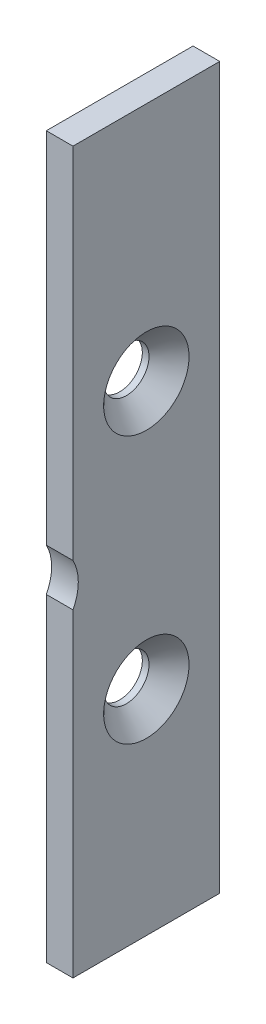
SolidWorks part; units mm, degrees
other "Preload Guide Rod End Stop"
ref_plane "Front Plane" through (0, 0, 0) normal (0, 0, 1) x (1, 0, 0)
ref_plane "Top Plane" through (0, 0, 0) normal (0, 1, 0) x (1, 0, 0)
ref_plane "Right Plane" through (0, 0, 0) normal (1, 0, 0) x (0, 0, -1)
sketch3d "End stop sheet sketch datum points"
  point P0 (58.2, -54.5, -33.5)
  point P1 (68.2, -54.5, -33.5)
  point P2 (58.2, -44.5, -33.5)
ref_plane "End stop sheet sketch plane" through (0, 0, -33.5) normal (0, 0, 1) x (1, 0, 0)
sketch "End stop sheet sketch" plane through (0, 0, -33.5) normal (0, 0, 1) x (1, 0, 0)
  line L0 (58.2, -54.5) -> (60.2, -54.5)
  line L1 (60.2, -54.5) -> (60.2, -0.5)
  line L2 (60.2, -0.5) -> (58.2, -0.5)
  line L3 (58.2, -0.5) -> (58.2, -54.5)
extrude "End stop sheet" add sketch "End stop sheet sketch" along normal blind 11 separate body
sketch3d "Screw end clearance sketch datum points"
  point P0 (58.1, -29, -19.5)
  point P1 (58.1, -19, -19.5)
  point P2 (58.1, -29, -9.5)
ref_plane "Screw end clearance sketch plane" through (58.1, 0, 0) normal (1, 0, 0) x (0, 0, -1)
sketch "Screw end clearance sketch" plane through (58.1, 0, 0) normal (1, 0, 0) x (0, 0, -1)
  circle A0 centre (19.5, -29) radius 3.4
extrude "Screw end clearance" cut sketch "Screw end clearance sketch" along normal blind 2.2
sketch3d "M3 countersunk clearance 1 bore profile datum points"
  point P0 (60.2, -18.5, -28)
  point P1 (60.2, -8.5, -28)
  point P2 (60.2, -18.5, -38)
ref_plane "M3 countersunk clearance 1 bore profile plane" through (60.2, 0, 0) normal (-1, 0, 0) x (0, 0, 1)
sketch "M3 countersunk clearance 1 bore profile" plane through (60.2, 0, 0) normal (-1, 0, 0) x (0, 0, 1)
  circle A0 centre (-28, -18.5) radius 1.7
extrude "M3 countersunk clearance 1 bore" cut sketch "M3 countersunk clearance 1 bore profile" along normal blind 2.2
sketch3d "M3 countersunk clearance 1 countersink axis line"
  line L0 (70.2, -18.5, -28) -> (50.2, -18.5, -28) construction
ref_axis "M3 countersunk clearance 1 countersink axis" through (70.2, -18.5, -28) along (-1, 0, 0)
sketch3d "M3 countersunk clearance 1 countersink profile datum points"
  point P0 (60.2, -18.5, -28)
  point P1 (60.2, -8.5, -28)
  point P2 (50.2, -18.5, -28)
ref_plane "M3 countersunk clearance 1 countersink profile plane" through (0, 0, -28) normal (0, 0, 1) x (1, 0, 0)
sketch "M3 countersunk clearance 1 countersink profile" plane through (0, 0, -28) normal (0, 0, 1) x (1, 0, 0)
  line L0 (60.2, -18.5) -> (60.2, -15.3)
  line L1 (60.2, -15.3) -> (58.7, -16.8)
  line L2 (58.7, -16.8) -> (58.7, -18.5)
  line L3 (58.7, -18.5) -> (60.2, -18.5)
revolve "M3 countersunk clearance 1 countersink" cut sketch "M3 countersunk clearance 1 countersink profile" angle 360 about axis through (70.2, -18.5, -28) along (-1, 0, 0)
sketch3d "M3 countersunk clearance 2 bore profile datum points"
  point P0 (60.2, -38.5, -28)
  point P1 (60.2, -28.5, -28)
  point P2 (60.2, -38.5, -38)
ref_plane "M3 countersunk clearance 2 bore profile plane" through (60.2, 0, 0) normal (-1, 0, 0) x (0, 0, 1)
sketch "M3 countersunk clearance 2 bore profile" plane through (60.2, 0, 0) normal (-1, 0, 0) x (0, 0, 1)
  circle A0 centre (-28, -38.5) radius 1.7
extrude "M3 countersunk clearance 2 bore" cut sketch "M3 countersunk clearance 2 bore profile" along normal blind 2.2
sketch3d "M3 countersunk clearance 2 countersink axis line"
  line L0 (70.2, -38.5, -28) -> (50.2, -38.5, -28) construction
ref_axis "M3 countersunk clearance 2 countersink axis" through (70.2, -38.5, -28) along (-1, 0, 0)
sketch3d "M3 countersunk clearance 2 countersink profile datum points"
  point P0 (60.2, -38.5, -28)
  point P1 (60.2, -28.5, -28)
  point P2 (50.2, -38.5, -28)
ref_plane "M3 countersunk clearance 2 countersink profile plane" through (0, 0, -28) normal (0, 0, 1) x (1, 0, 0)
sketch "M3 countersunk clearance 2 countersink profile" plane through (0, 0, -28) normal (0, 0, 1) x (1, 0, 0)
  line L0 (60.2, -38.5) -> (60.2, -35.3)
  line L1 (60.2, -35.3) -> (58.7, -36.8)
  line L2 (58.7, -36.8) -> (58.7, -38.5)
  line L3 (58.7, -38.5) -> (60.2, -38.5)
revolve "M3 countersunk clearance 2 countersink" cut sketch "M3 countersunk clearance 2 countersink profile" angle 360 about axis through (70.2, -38.5, -28) along (-1, 0, 0)
